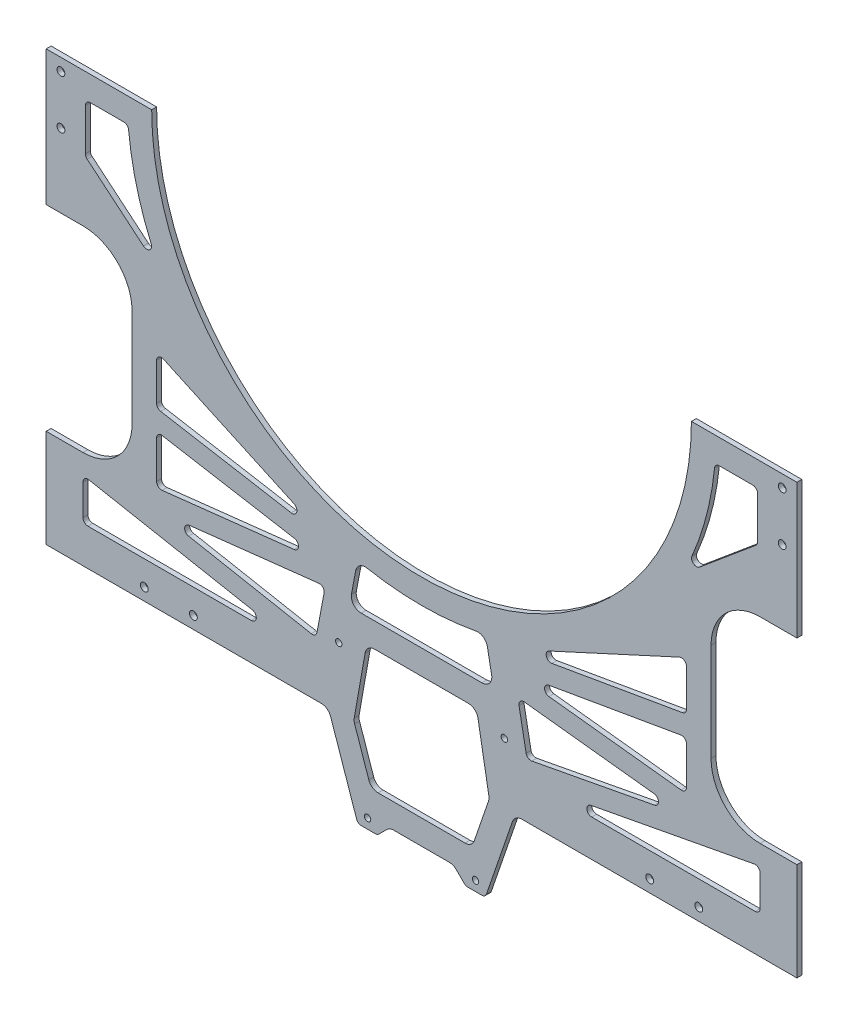
SolidWorks part; units mm, degrees
material "环氧树脂FR-4"
ref_plane "前视基准面" through (0, 0, 0) normal (0, 0, 1) x (1, 0, 0)
ref_plane "上视基准面" through (0, 0, 0) normal (0, 1, 0) x (1, 0, 0)
ref_plane "右视基准面" through (0, 0, 0) normal (1, 0, 0) x (0, 0, -1)
sketch "草图1" plane through (0, 0, 0) normal (0, 0, 1) x (1, 0, 0)
  line L1 (-153, 87.5) -> (153, 87.5)
  line L2 (-153, 87.5) -> (-153, -87.5)
  line L3 (-153, -87.5) -> (153, -87.5)
  line L4 (153, 87.5) -> (153, -87.5)
  line L5 (-153, 87.5) -> (153, -87.5) construction
  line L6 (-153, -87.5) -> (153, 87.5) construction
  point P0 (0, 0)
  dimension "D1" = 306
  dimension "D2" = 175
extrude "凸台-拉伸1" add sketch "草图1" along normal blind 2
sketch "草图2" plane through (0, 0, 2) normal (0, 0, 1) x (1, 0, 0)
  line L0 (153, 87.5) -> (-153, 87.5) construction
  line L1 (-153, 87.5) -> (-153, -87.5) construction
  line L2 (-153, 32.5) -> (-118, 32.5)
  line L3 (-153, 32.5) -> (-153, -47.5)
  line L4 (-153, -47.5) -> (-118, -47.5)
  line L5 (-118, 32.5) -> (-118, -47.5)
  line L6 (-153, -87.5) -> (153, -87.5) construction
  line L7 (0, -55) -> (0, 55) construction
  line L8 (153, -47.5) -> (118, -47.5)
  line L9 (118, 32.5) -> (118, -47.5)
  line L10 (153, 32.5) -> (118, 32.5)
  line L11 (153, 32.5) -> (153, -47.5)
  circle A0 centre (0, 87.5) radius 110
  dimension "D1" = 220
  dimension "D2" = 0
  dimension "D3" = 40
  dimension "D4" = 80
  dimension "D5" = 35
extrude "切除-拉伸1" cut sketch "草图2" against normal through all
fillet "圆角1" radius 20 4 edges at (118, -47.5, 1) (118, 32.5, 1) (-118, -47.5, 1) (-118, 32.5, 1)
sketch "草图3" plane through (0, 0, 2) normal (0, 0, 1) x (1, 0, 0)
  line L0 (-153, -87.5) -> (153, -87.5) construction
  line L1 (153, -87.5) -> (153, -47.5) construction
  point P0 (113, -82.5)
  point P5 (93, -82.5)
  dimension "D1" = 5
  dimension "D2" = 40
  dimension "D4" = 20
  dimension "D3" = 2
hole_wizard "Ø3.2 (3.2) 直径孔1" positions "3D草图1" profile "草图4" hole size "Ø3.2" standard "GB" end condition through all
sketch3d "3D草图1"
  point P0 (113, -82.5, 2)
  point P3 (93, -82.5, 2)
sketch "草图4" plane through (113, -82.5, 2) normal (1, 0, 0) x (0, -1, 0)
  line L0 (0, 0) -> (0, 2)
  line L1 (0, 2) -> (1.6, 2)
  line L2 (1.6, 2) -> (1.6, 0)
  line L5 (1.6, 0) -> (0, 0)
  line L11 (0, -6.35) -> (0, 107.95) construction
  dimension "通孔孔直径" = 3.2
  dimension "通孔孔深度" = 2
mirror "镜向1" about plane through (0, 0, 0) normal (1, 0, 0) of "Ø3.2 (3.2) 直径孔1"
sketch "草图5" plane through (0, 0, 2) normal (0, 0, 1) x (1, 0, 0)
  line L0 (-153, -87.5) -> (153, -87.5) construction
  line L1 (-38, -87.5) -> (38, -87.5)
  line L2 (-38, -87.5) -> (-38, -122.5)
  line L3 (-38, -122.5) -> (38, -122.5)
  line L4 (38, -87.5) -> (38, -122.5)
  dimension "D1" = 0
  dimension "D2" = 35
  dimension "D3" = 38
  dimension "D4" = 76
extrude "凸台-拉伸2" add sketch "草图5" against normal up to surface (2 mm away) up to face at (-111.4, -82.5, 0)
sketch "草图6" plane through (0, 0, 2) normal (0, 0, 1) x (1, 0, 0)
  line L1 (-153, -87.5) -> (-38, -87.5) construction
  line L2 (38, -87.5) -> (153, -87.5) construction
  point P0 (-33.75, -62.5)
  point P1 (33.75, -62.5)
  point P2 (-22, -118.5)
  point P4 (22, -118.5)
  dimension "D1" = 33.75
  dimension "D2" = 67.5
  dimension "D3" = 25
  dimension "D4" = 56
  dimension "D5" = 0
  dimension "D6" = 22
  dimension "D7" = 22
  dimension "D8" = 25
hole_wizard "Ø2.6 (2.6) 直径孔1" positions "3D草图2" profile "草图7" hole size "Ø2.6" standard "GB" end condition through all
sketch3d "3D草图2"
  point P0 (-33.75, -62.5, 2)
  point P3 (33.75, -62.5, 2)
  point P6 (-22, -118.5, 2)
  point P9 (22, -118.5, 2)
sketch "草图7" plane through (-33.75, -62.5, 2) normal (1, 0, 0) x (0, -1, 0)
  line L0 (0, 0) -> (0, 2)
  line L1 (0, 2) -> (1.3, 2)
  line L2 (1.3, 2) -> (1.3, 0)
  line L5 (1.3, 0) -> (0, 0)
  line L11 (0, -6.35) -> (0, 107.95) construction
  dimension "通孔孔直径" = 2.6
  dimension "通孔孔深度" = 2
sketch "草图8" plane through (0, 0, 2) normal (0, 0, 1) x (1, 0, 0)
  line L4 (38, -122.5) -> (26, -122.5)
  line L5 (38, -122.5) -> (-38, -122.5) construction
  line L6 (26, -122.5) -> (38, -87.5)
  line L7 (38, -87.5) -> (38, -122.5)
  line L8 (-38, -87.5) -> (-26, -122.5)
  line L9 (-38, -122.5) -> (38, -122.5) construction
  line L10 (-26, -122.5) -> (-38, -122.5)
  line L11 (-38, -122.5) -> (-38, -87.5)
  line L12 (-18, -122.5) -> (-13, -117.5)
  line L13 (-13, -117.5) -> (13, -117.5)
  line L14 (13, -117.5) -> (18, -122.5)
  line L15 (18, -122.5) -> (-18, -122.5)
  point P20 (13.521, -117.5)
  point P22 (-25.7309, -122.5)
  dimension "D1" = 12
  dimension "D2" = 12
  dimension "D3" = 5
  dimension "D4" = 8
  dimension "D5" = 8
  dimension "D6" = 45
  dimension "D7" = 45
extrude "切除-拉伸2" cut sketch "草图8" against normal through all
fillet "圆角2" radius 2 4 edges at (26, -122.5, 1) (18, -122.5, 1) (-18, -122.5, 1) (-26, -122.5, 1)
fillet "圆角3" radius 4 4 edges at (38, -87.5, 1) (13, -117.5, 1) (-13, -117.5, 1) (-38, -87.5, 1)
sketch "草图9" plane through (0, 0, 2) normal (0, 0, 1) x (1, 0, 0)
  line L0 (-138, -55.5) -> (-138, -72.5)
  line L1 (-138, -72.5) -> (-48, -72.5)
  line L2 (-17.0039, -117.9054) -> (-27.6139, -86.9595)
  line L3 (-21.4981, -104.7973) -> (-27.2793, -87.9354)
  line L4 (-17.7143, -107.5) -> (17.7143, -107.5)
  line L5 (27.6139, -86.9595) -> (17.0039, -117.9054)
  line L6 (27.2793, -87.9354) -> (21.4981, -104.7973)
  line L7 (11.3431, -117.5) -> (-11.3431, -117.5) construction
  line L8 (-48, -72.5) -> (-138, -55.5)
  line L9 (-27.4348, -85.9435) -> (-23.0022, -60.8054)
  line L10 (-19.063, -57.5) -> (19.063, -57.5)
  line L11 (23.0022, -60.8054) -> (27.4348, -85.9435)
  line L12 (-153, -47.5) -> (-153, -87.5) construction
  line L13 (-153, -87.5) -> (-40.8571, -87.5) construction
  line L14 (-108, -53.0252) -> (-43, -65.303)
  line L15 (-43, -65.303) -> (-39.2222, -45.303)
  line L16 (-39.2222, -45.303) -> (-108, -53.0252)
  line L17 (-108, -24.9749) -> (-108, -44.9749)
  line L18 (-108, -44.9749) -> (-38, -37.1155)
  line L19 (-38, -37.1155) -> (-108, -24.9749)
  line L21 (-118, -27.5) -> (-118, 12.5) construction
  line L22 (-108, 3.1445) -> (-108, -16.8555)
  line L23 (-108, -16.8555) -> (-38, -28.9961)
  line L24 (-38, -28.9961) -> (-108, 3.1445)
  arc A0 (-23.0022, -60.8054) -> (-19.063, -57.5) centre (-19.063, -61.5) cw
  arc A1 (19.063, -57.5) -> (23.0022, -60.8054) centre (19.063, -61.5) cw
  arc A2 (27.2793, -87.9354) -> (27.4348, -85.9435) centre (23.4955, -86.6381) ccw
  arc A3 (17.7143, -107.5) -> (21.4981, -104.7973) centre (17.7143, -103.5) ccw
  arc A4 (-21.4981, -104.7973) -> (-17.7143, -107.5) centre (-17.7143, -103.5) ccw
  arc A5 (-27.2793, -87.9354) -> (-27.4348, -85.9435) centre (-23.4955, -86.6381) cw
  point P25 (-27.6139, -86.9595)
  dimension "D8" = 4
  dimension "D3" = 10
  dimension "D4" = 100
  dimension "D5" = 100
  dimension "D6" = 50
  dimension "D7" = 0
  dimension "D9" = 15
  dimension "D10" = 90
  dimension "12" = 15
  dimension "D11" = 17
  dimension "D12" = 8
  dimension "D13" = 20
  dimension "D14" = 65
  dimension "D15" = 30
  dimension "D16" = 8
  dimension "D17" = 20
  dimension "D18" = 80
  dimension "D19" = 10
  dimension "D20" = 8
  dimension "D21" = 20
  dimension "D22" = 0
  dimension "D1" = 10
  dimension "D2" = 10
extrude "切除-拉伸3" cut sketch "草图9" against normal through all
fillet "圆角4" radius 2 12 edges at (-38, -28.9961, 1) (-38, -37.1155, 1) (-39.2222, -45.303, 1) (-43, -65.303, 1) (-48, -72.5, 1) (-108, -16.8555, 1) (-108, 3.1445, 1) (-108, -24.9749, 1) (-108, -44.9749, 1) (-108, -53.0252, 1) (-138, -72.5, 1) (-138, -55.5, 1)
mirror "镜向2" about plane through (0, 0, 0) normal (1, 0, 0) of "圆角4", "切除-拉伸3"
sketch "草图10" plane through (0, 0, 2) normal (0, 0, 1) x (1, 0, 0)
  line L0 (-29.4604, -47.5) -> (-26.085, -29.6306)
  line L1 (-29.4604, -47.5) -> (29.4604, -47.5)
  line L2 (29.4604, -47.5) -> (26.085, -29.6306)
  line L4 (42.6288, -63.3377) -> (39.7248, -47.9638) construction
  line L5 (19.063, -57.5) -> (-19.063, -57.5) construction
  line L6 (-42.6288, -63.3377) -> (-39.7248, -47.9638) construction
  arc A0 (-26.085, -29.6306) -> (26.085, -29.6306) centre (0, 87.5) ccw
  dimension "D1" = 240
  dimension "D2" = 10
  dimension "D3" = 10
  dimension "D4" = 10
extrude "切除-拉伸4" cut sketch "草图10" against normal through all
fillet "圆角5" radius 4 4 edges at (29.4604, -47.5, 1) (26.085, -29.6306, 1) (-29.4604, -47.5, 1) (-26.085, -29.6306, 1)
sketch "草图11" plane through (0, 0, 2) normal (0, 0, 1) x (1, 0, 0)
  line L0 (153, 32.5) -> (153, 87.5) construction
  line L1 (153, 87.5) -> (110, 87.5) construction
  point P0 (147, 82.5)
  point P6 (147, 62.5)
  dimension "D1" = 6
  dimension "D2" = 5
  dimension "D4" = 20
  dimension "D3" = 2
hole_wizard "Ø3.2 (3.2) 直径孔2" positions "3D草图3" profile "草图12" hole size "Ø3.2" standard "GB" end condition through all
sketch3d "3D草图3"
  point P0 (147, 82.5, 2)
  point P3 (147, 62.5, 2)
sketch "草图12" plane through (147, 82.5, 2) normal (1, 0, 0) x (0, -1, 0)
  line L0 (0, 0) -> (0, 2)
  line L1 (0, 2) -> (1.6, 2)
  line L2 (1.6, 2) -> (1.6, 0)
  line L5 (1.6, 0) -> (0, 0)
  line L11 (0, -6.35) -> (0, 107.95) construction
  dimension "通孔孔直径" = 3.2
  dimension "通孔孔深度" = 2
mirror "镜向3" about plane through (0, 0, 0) normal (1, 0, 0) of "Ø3.2 (3.2) 直径孔2"
sketch "草图13" plane through (0, 0, 2) normal (0, 0, 1) x (1, 0, 0)
  line L0 (-137, 77.5) -> (-119.5826, 77.5)
  line L1 (-137, 77.5) -> (-137, 57.5)
  line L3 (-153, 87.5) -> (-153, 32.5) construction
  line L4 (-110, 87.5) -> (-153, 87.5) construction
  line L6 (-137, 57.5) -> (-106.3124, 31.8432)
  arc A0 (-119.5826, 77.5) -> (-106.3124, 31.8432) centre (0, 87.5) ccw
  dimension "D1" = 240
  dimension "D2" = 16
  dimension "D3" = 10
  dimension "D4" = 20
  dimension "D5" = 40
extrude "切除-拉伸5" cut sketch "草图13" against normal through all
fillet "圆角7" radius 2 4 edges at (-106.3124, 31.8432, 1) (-137, 57.5, 1) (-119.5826, 77.5, 1) (-137, 77.5, 1)
mirror "镜向4" about plane through (0, 0, 0) normal (1, 0, 0) of "圆角7", "切除-拉伸5"
